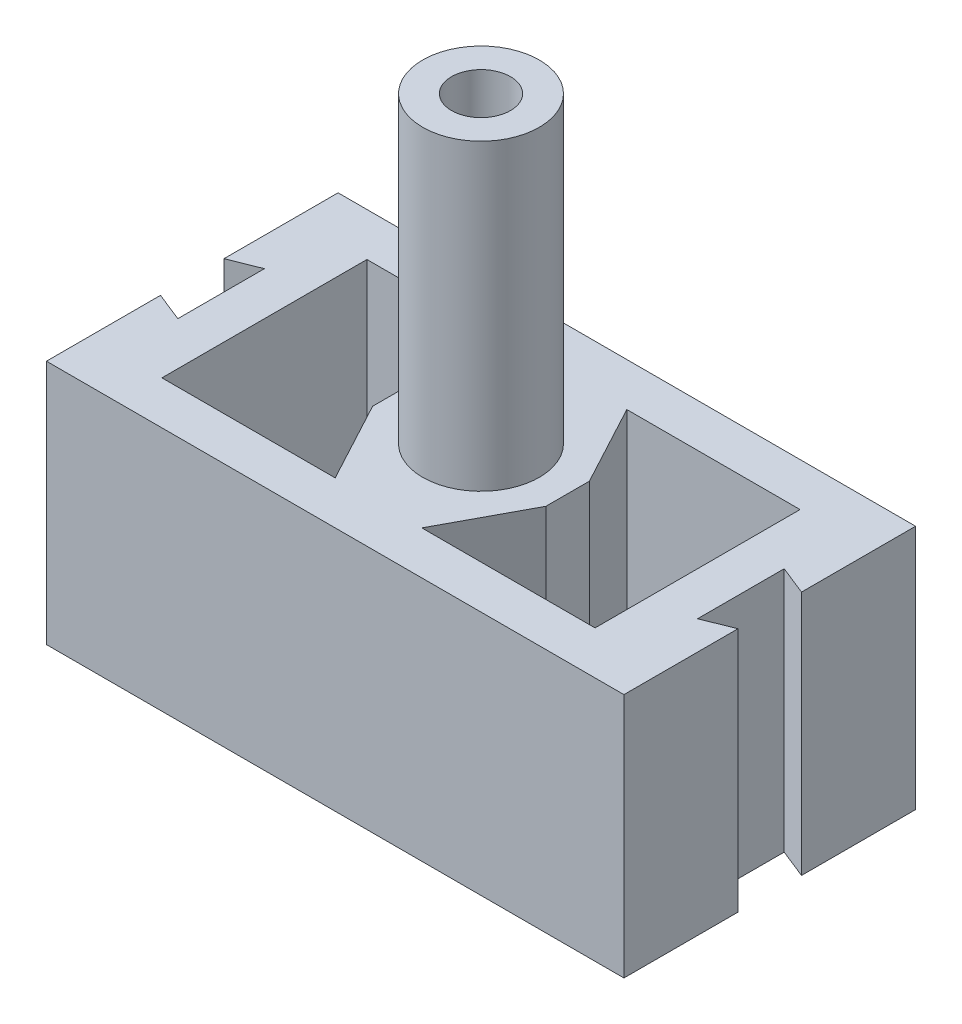
SolidWorks part; units mm, degrees
ref_plane "Front Plane" through (0, 0, 0) normal (0, 0, 1) x (1, 0, 0)
ref_plane "Top Plane" through (0, 0, 0) normal (0, 1, 0) x (1, 0, 0)
ref_plane "Right Plane" through (0, 0, 0) normal (1, 0, 0) x (0, 0, -1)
sketch "Sketch1" plane through (0, 0, 0) normal (0, 1, 0) x (1, 0, 0)
  line L0 (-50, 5.5) -> (-45, 7.5)
  line L1 (-50, -25.25) -> (50, -25.25)
  line L2 (-50, -25.25) -> (-50, 25.25)
  line L3 (-50, 25.25) -> (50, 25.25)
  line L4 (50, -25.25) -> (50, 25.25)
  line L5 (-50, -25.25) -> (50, 25.25) construction
  line L6 (-50, 25.25) -> (50, -25.25) construction
  line L7 (-45, 7.5) -> (-45, -7.5)
  line L8 (-45, -7.5) -> (-50, -5.5)
  line L9 (-45, -7.5) -> (-50, -25.25) construction
  line L10 (-45, 7.5) -> (-50, 25.25) construction
  line L11 (0, 25.25) -> (0, -25.25) construction
  line L12 (-50, 5.5) -> (-50, -5.5)
  line L13 (50, 5.5) -> (45, 7.5)
  line L14 (45, 7.5) -> (45, -7.5)
  line L15 (45, -7.5) -> (50, -5.5)
  line L16 (50, 5.5) -> (50, -5.5)
  circle A0 centre (0, 0) radius 3.1
  point P0 (0, 0)
  dimension "D7" = 6.2
  dimension "D1" = 50.5
  dimension "D2" = 100
  dimension "D3" = 15
  dimension "D4" = 2
  dimension "D5" = 5
  dimension "D6" = 50.5
extrude "Boss-Extrude1" add sketch "Sketch1" along normal blind 42.5 contours L15 L14 L13 L4 L3 L2 L0 L7 L8 L1 A0
sketch "Sketch2" plane through (0, 42.5, 0) normal (0, 1, 0) x (1, 0, 0)
  circle A0 centre (0, 0) radius 5.1
  circle A1 centre (0, 0) radius 10.1
  circle A2 centre (0, 0) radius 3.1 construction
  dimension "D1" = 2
  dimension "D2" = 5
extrude "Boss-Extrude2" add sketch "Sketch2" along normal blind 52.5
sketch "Sketch3" plane through (0, 42.5, 0) normal (0, 1, 0) x (1, 0, 0)
  line L0 (0, 25.25) -> (0, -25.25) construction
  line L1 (-50, 25.25) -> (50, 25.25) construction
  line L2 (-50, -25.25) -> (50, -25.25) construction
  line L3 (-37.5, -17.75) -> (-37.5, 17.75)
  line L4 (-37.5, 17.75) -> (-7.5, 17.75)
  line L5 (-7.5, 17.75) -> (-15, 3.7694)
  line L6 (-15, 3.7694) -> (-15, -3.7694)
  line L7 (-15, -3.7694) -> (-7.5, -17.75)
  line L8 (-7.5, -17.75) -> (-37.5, -17.75)
  line L9 (-45, 7.5) -> (-45, -7.5) construction
  line L10 (-50, 25.25) -> (-37.5, 17.75) construction
  line L11 (-37.5, -17.75) -> (-50, -25.25) construction
  line L12 (15, -3.7694) -> (7.5, -17.75)
  line L13 (15, 3.7694) -> (15, -3.7694)
  line L14 (7.5, 17.75) -> (15, 3.7694)
  line L15 (37.5, 17.75) -> (7.5, 17.75)
  line L16 (37.5, -17.75) -> (37.5, 17.75)
  line L17 (7.5, -17.75) -> (37.5, -17.75)
  circle A0 centre (0, 0) radius 10.1 construction
  dimension "D5" = 15
  dimension "D1" = 7.5
  dimension "D2" = 15
  dimension "D3" = 7.5
  dimension "D4" = 7.5
extrude "Cut-Extrude1" cut sketch "Sketch3" against normal up to surface (42.5 mm away) up to face at (0, 0, 3.1)
